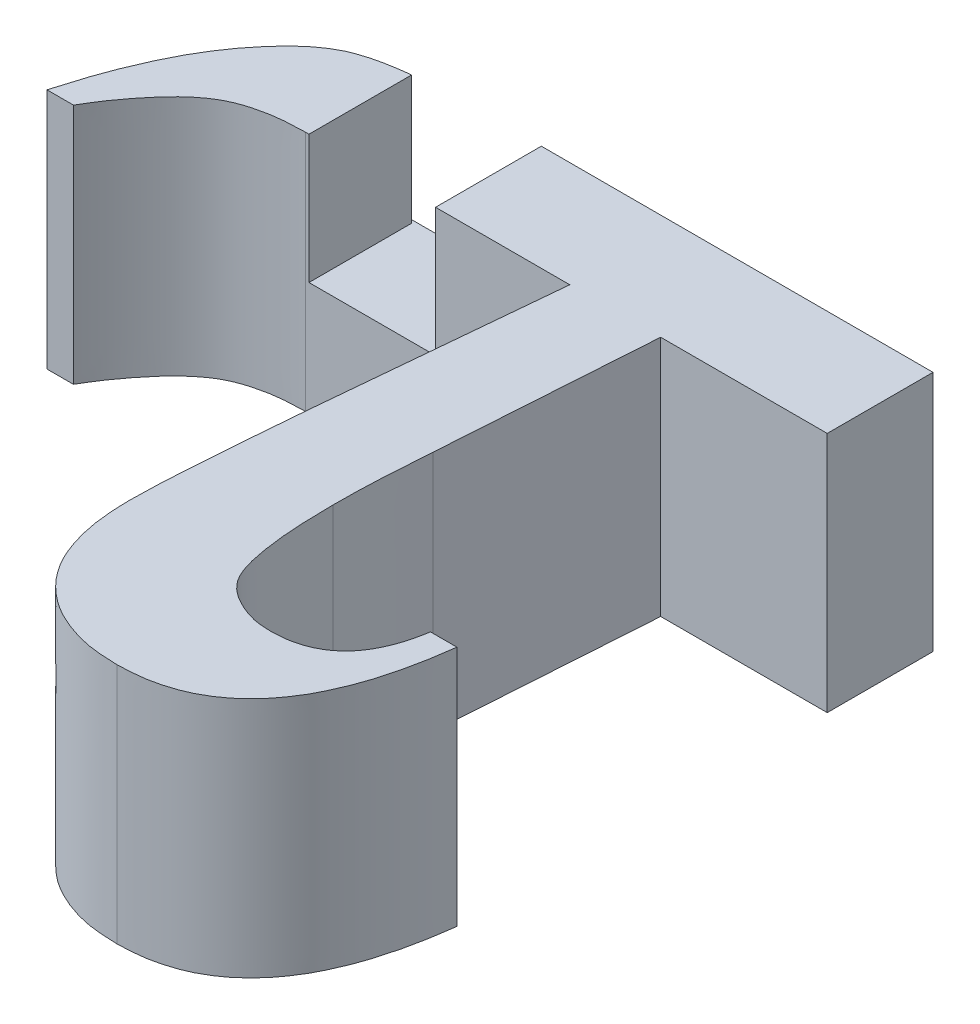
SolidWorks part; units mm, degrees
ref_plane "Front Plane" through (0, 0, 0) normal (0, 0, 1) x (1, 0, 0)
ref_plane "Top Plane" through (0, 0, 0) normal (0, 1, 0) x (1, 0, 0)
ref_plane "Right Plane" through (0, 0, 0) normal (1, 0, 0) x (0, 0, -1)
sketch "Sketch2" plane through (0, 0, 0) normal (0, 1, 0) x (1, 0, 0)
  line L0 (0, 0) -> (31.8, 0) construction
  text T0 "π" font "Times New Roman" height 50
extrude "Boss-Extrude1" add sketch "Sketch2" along normal blind 12.7
sketch "Sketch3" plane through (0, 12.7, 0) normal (0, 1, 0) x (1, 0, 0)
  line L0 (9.5914, 28.4722) -> (16.2373, 28.4722)
  line L2 (9.5914, 28.4722) -> (16.2373, 28.4722)
  line L3 (9.5914, 28.4722) -> (9.5914, 34.59)
  line L4 (9.5914, 34.59) -> (16.2373, 34.59)
  line L5 (16.2373, 28.4722) -> (16.2373, 34.59)
  line M2 (36.8056, 34.0278) -> (13.2921, 34.0278)
  spline M3 degree 3 poles (13.2921, 34.0278) (12.9268, 34.0254) (12.225, 34.021) (11.2113, 33.9939) (10.286, 33.9219) (9.4446, 33.8558) (8.696, 33.7434) (8.0271, 33.6193) (7.4491, 33.4555) (6.7726, 33.2249) (5.9967, 32.7859) (5.1185, 32.059) (4.2591, 31.116) (3.404, 29.9807) (2.6041, 28.6426) (1.8863, 27.1199) (1.2293, 25.4311) (0.8771, 24.2326) (0.6944, 23.6111) knots 0 0 0 0 0.060025 0.115321 0.166552 0.2125 0.253933 0.290879 0.324185 0.352567 0.408153 0.469409 0.53921 0.617298 0.702602 0.794837 0.89361 1 1 1 1
  spline M7 degree 3 poles (11.8056, 28.4722) (11.7481, 27.7376) (11.6371, 26.3176) (11.4106, 24.2683) (11.1948, 22.3666) (10.9266, 20.6249) (10.6667, 19.033) (10.3552, 17.603) (10.0526, 16.3164) (9.5835, 14.8145) (8.9128, 13.0516) (7.9241, 11.0191) (6.7785, 9.0096) (5.8809, 7.7333) (5.4253, 7.0855) knots 0 0 0 0 0.097498 0.188461 0.272819 0.350727 0.421621 0.486203 0.54436 0.596439 0.694303 0.793629 0.895262 1 1 1 1
  spline M8 degree 3 poles (5.4253, 7.0855) (5.13, 6.6718) (4.5879, 5.9124) (3.9752, 4.7856) (3.5617, 3.8003) (3.4998, 3.1676) (3.4722, 2.8863) knots 0 0 0 0 0.324491 0.595557 0.820162 1 1 1 1
  spline M9 degree 3 poles (3.4722, 2.8863) (3.4869, 2.6315) (3.5155, 2.1338) (3.7376, 1.428) (4.1059, 0.798) (4.6238, 0.2715) (5.2348, -0.159) (5.9273, -0.4698) (6.6815, -0.6565) (7.2074, -0.6816) (7.4761, -0.6944) knots 0 0 0 0 0.127152 0.248345 0.365828 0.488548 0.614409 0.737368 0.865811 1 1 1 1
  spline M10 degree 3 poles (7.4761, -0.6944) (7.8336, -0.6765) (8.5263, -0.6416) (9.5051, -0.2852) (10.3581, 0.2921) (10.958, 0.9642) (11.3788, 1.6424) (11.6867, 2.3016) (12.004, 3.0856) (12.3039, 4.0112) (12.5902, 5.0744) (12.8869, 6.2704) (13.1648, 7.603) (13.4365, 9.0867) (13.7156, 10.7451) (13.9545, 12.618) (14.2083, 14.7114) (14.4428, 17.0306) (14.6708, 19.5734) (14.8861, 22.3406) (15.0921, 25.3319) (15.2145, 27.4015) (15.2778, 28.4722) knots 0 0 0 0 0.033392 0.064699 0.096195 0.129076 0.148263 0.170853 0.197164 0.2275 0.261958 0.300352 0.342967 0.389507 0.441724 0.500547 0.566432 0.639355 0.718994 0.805699 0.899478 1 1 1 1
extrude "Cut-Extrude2" cut sketch "Sketch3" against normal blind 12.7 and the other way through all contours L0 M7 M8 M9 M10 | L0 L5 L3 M2 M3
sketch "Sketch4" plane through (16.2373, 0, 0) normal (-1, 0, 0) x (0, 0, 1)
  line L1 (-34.0278, 0) -> (-28.4722, 0)
  line L2 (-34.0278, 0) -> (-34.0278, 5.9542)
  line L3 (-34.0278, 5.9542) -> (-28.4722, 5.9542)
  line L4 (-28.4722, 0) -> (-28.4722, 5.9542)
  point P5 (-28.4722, 0)
extrude "Boss-Extrude2" add sketch "Sketch4" along normal blind 7
